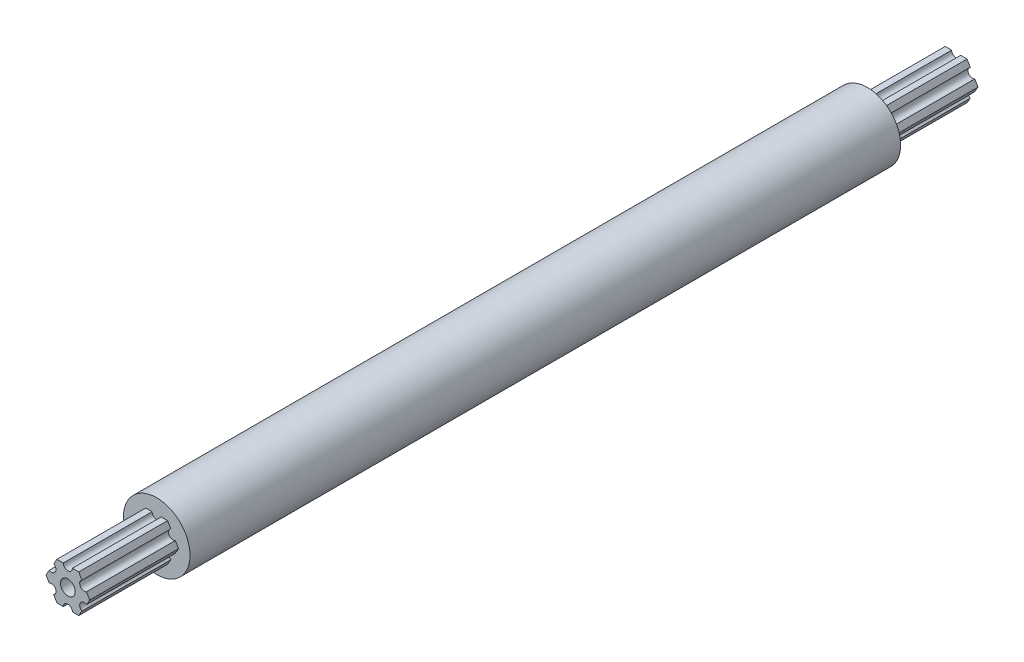
SolidWorks part; units mm, degrees
ref_plane "Front Plane" through (0, 0, 0) normal (0, 0, 1) x (1, 0, 0)
ref_plane "Top Plane" through (0, 0, 0) normal (0, 1, 0) x (1, 0, 0)
ref_plane "Right Plane" through (0, 0, 0) normal (1, 0, 0) x (0, 0, -1)
sketch "Sketch1" plane through (0, 0, 0) normal (0, 0, 1) x (1, 0, 0)
  line L0 (-3.7465, 6.4891) -> (3.7465, 6.4891) construction
  line L1 (7.493, 0) -> (6.3965, 1.8991)
  line L2 (3.7465, 6.4891) -> (1.5536, 6.4891)
  line L3 (-3.7465, 6.4891) -> (-4.843, 4.59)
  line L4 (-7.493, 0) -> (-6.3965, -1.8991)
  line L5 (-3.7465, -6.4891) -> (-1.5536, -6.4891)
  line L6 (3.7465, -6.4891) -> (4.843, -4.59)
  line L7 (-1.5536, 6.4891) -> (-3.7465, 6.4891)
  line L8 (3.7465, 6.4891) -> (7.493, 0) construction
  line L9 (7.493, 0) -> (3.7465, -6.4891) construction
  line L10 (3.7465, -6.4891) -> (-3.7465, -6.4891) construction
  line L11 (-3.7465, -6.4891) -> (-7.493, 0) construction
  line L12 (-7.493, 0) -> (-3.7465, 6.4891) construction
  line L13 (-6.3965, 1.8991) -> (-7.493, 0)
  line L14 (-4.843, -4.59) -> (-3.7465, -6.4891)
  line L15 (1.5536, -6.4891) -> (3.7465, -6.4891)
  line L16 (6.3965, -1.8991) -> (7.493, 0)
  line L17 (4.843, 4.59) -> (3.7465, 6.4891)
  circle A0 centre (0, 0) radius 6.4891 construction
  circle A1 centre (0, 0) radius 2.54
  arc A2 (-1.5536, 6.4891) -> (1.5536, 6.4891) centre (0, 6.4891) ccw
  arc A3 (4.843, 4.59) -> (6.3965, 1.8991) centre (5.6198, 3.2446) ccw
  arc A4 (6.3965, -1.8991) -> (4.843, -4.59) centre (5.6197, -3.2446) ccw
  arc A5 (1.5536, -6.4891) -> (-1.5536, -6.4891) centre (0, -6.4891) ccw
  arc A6 (-4.843, -4.59) -> (-6.3965, -1.8991) centre (-5.6198, -3.2446) ccw
  arc A7 (-6.3965, 1.8991) -> (-4.843, 4.59) centre (-5.6197, 3.2446) ccw
  point P41 (0, 0)
  dimension "D2" = 14.986
  dimension "D3" = 5.08
  dimension "D1" = 6
extrude "Boss-Extrude1" add sketch "Sketch1" along normal blind 304.8
ref_plane "Plane1" through (0, 0, 152.4) normal (0, 0, -1) x (-1, 0, 0)
sketch "Sketch2" plane through (0, 0, 152.4) normal (0, 0, -1) x (-1, 0, 0)
  circle A0 centre (0, 0) radius 11.43
  dimension "D1" = 22.86
extrude "Boss-Extrude2" add sketch "Sketch2" along normal mid plane 243.84
